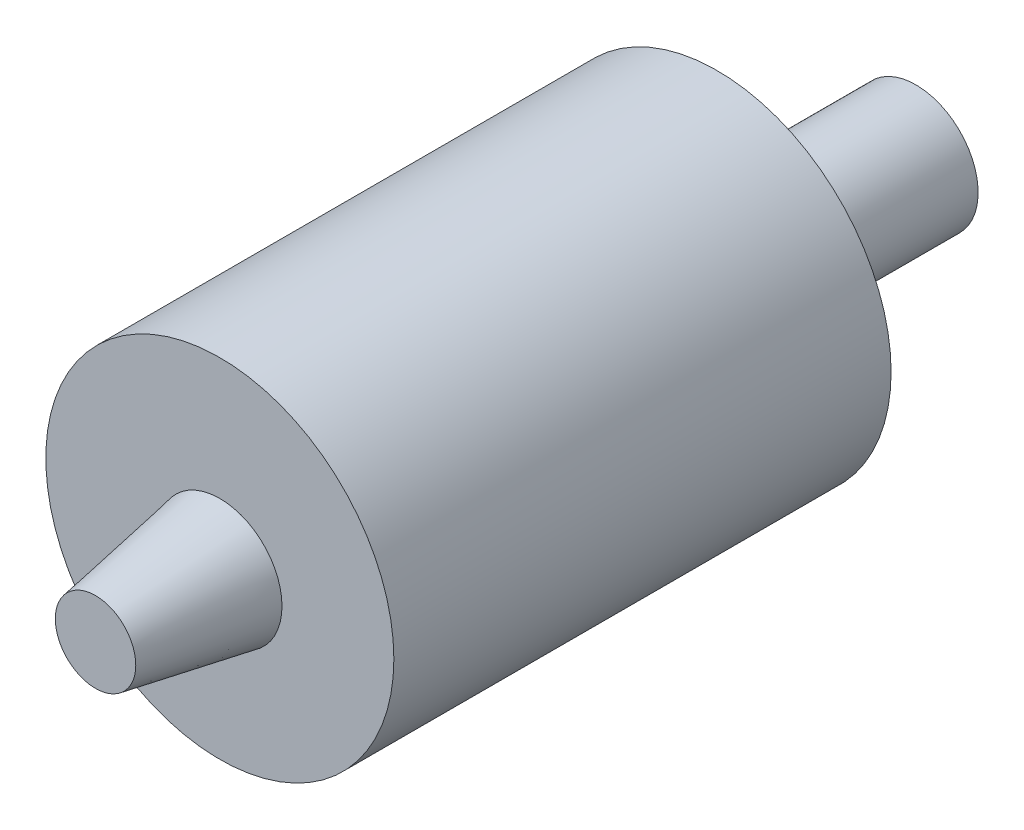
SolidWorks part; units mm, degrees
ref_plane "Ebene vorne" through (0, 0, 0) normal (0, 0, 1) x (1, 0, 0)
ref_plane "Ebene oben" through (0, 0, 0) normal (0, 1, 0) x (1, 0, 0)
ref_plane "Ebene rechts" through (0, 0, 0) normal (1, 0, 0) x (0, 0, -1)
sketch "Skizze1" plane through (0, 0, 0) normal (0, 0, 1) x (1, 0, 0)
  circle A0 centre (0, 0) radius 14
  dimension "D1" = 28
extrude "Aufsatz-Linear austragen1" add sketch "Skizze1" along normal blind 40
sketch "Skizze2" plane through (0, 0, 0) normal (0, 0, -1) x (-1, 0, 0)
  circle A0 centre (0, 0) radius 5
extrude "Aufsatz-Linear austragen2" add sketch "Skizze2" along normal blind 16
sketch "Skizze3" plane through (0, 0, 40) normal (0, 0, 1) x (1, 0, 0)
  circle A0 centre (0, -0.8171) radius 5
extrude "Aufsatz-Linear austragen3" add sketch "Skizze3" along normal blind 10 draft 10 contours A0
